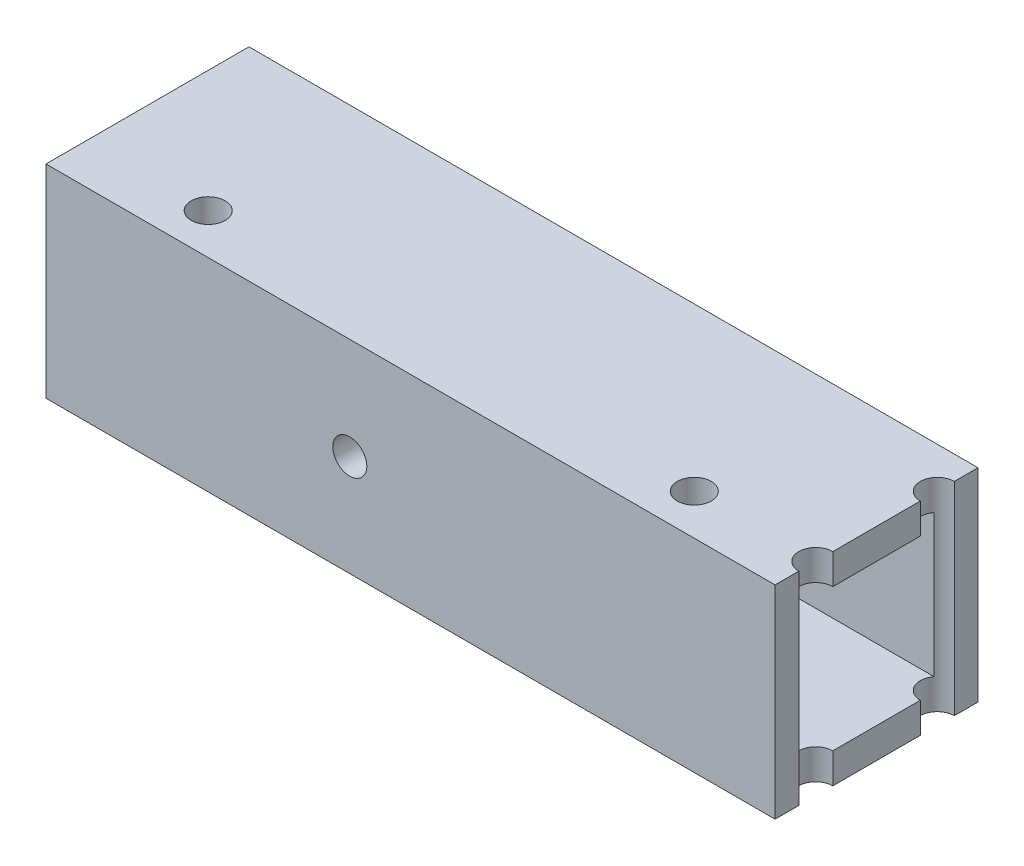
SolidWorks part; units mm, degrees
ref_plane "Front Plane" through (0, 0, 0) normal (0, 0, 1) x (1, 0, 0)
ref_plane "Top Plane" through (0, 0, 0) normal (0, 1, 0) x (1, 0, 0)
ref_plane "Right Plane" through (0, 0, 0) normal (1, 0, 0) x (0, 0, -1)
ref_plane "Plane1" through (0, -110.3, 0) normal (0, -1, 0) x (1, 0, 0)
sketch "Sketch1" plane through (0, -110.3, 0) normal (0, -1, 0) x (1, 0, 0)
  line L0 (-150, 132.8) -> (-150, 107.2)
  line L1 (-150, 107.2) -> (-30, 107.2)
  line L2 (-30, 112.8) -> (-30, 127.2)
  line L3 (-30, 132.8) -> (-150, 132.8)
  arc A0 (-30, 107.2) -> (-30, 112.8) centre (-30, 110) ccw
  arc A1 (-30, 127.2) -> (-30, 132.8) centre (-30, 130) ccw
extrude "Boss-Extrude1" add sketch "Sketch1" against normal blind 5
sketch "Sketch2" plane through (0, 0, 107.2) normal (0, 0, -1) x (-1, 0, 0)
  line L0 (30, -110.3) -> (30, -105.3)
  line L1 (30, -105.3) -> (150, -105.3)
  line L2 (150, -105.3) -> (150, -110.3)
  line L3 (150, -110.3) -> (30, -110.3)
extrude "Boss-Extrude2" add sketch "Sketch2" along normal blind 3.9
sketch "Sketch3" plane through (0, 0, 132.8) normal (0, 0, 1) x (1, 0, 0)
  line L0 (-30, -110.3) -> (-150, -110.3)
  line L1 (-150, -110.3) -> (-150, -105.3)
  line L2 (-150, -105.3) -> (-30, -105.3)
  line L3 (-30, -105.3) -> (-30, -110.3)
extrude "Boss-Extrude3" add sketch "Sketch3" along normal blind 3.9
sketch "Sketch4" plane through (0, -110.3, 0) normal (0, -1, 0) x (1, 0, 0)
  line L0 (-32.2249, 131.7) -> (-150, 131.7)
  line L1 (-150, 131.7) -> (-150, 136.7)
  line L2 (-150, 136.7) -> (-30, 136.7)
  line L3 (-30, 136.7) -> (-30, 132.8)
  arc A0 (-30, 132.8) -> (-32.2249, 131.7) centre (-30, 130) cw
extrude "Boss-Extrude4" add sketch "Sketch4" along normal blind 23.4
sketch "Sketch5" plane through (0, -110.3, 0) normal (0, -1, 0) x (1, 0, 0)
  line L0 (-150, 108.3) -> (-32.2249, 108.3)
  line L1 (-30, 107.2) -> (-30, 103.3)
  line L2 (-30, 103.3) -> (-150, 103.3)
  line L3 (-150, 103.3) -> (-150, 108.3)
  arc A0 (-32.2249, 108.3) -> (-30, 107.2) centre (-30, 110) cw
extrude "Boss-Extrude5" add sketch "Sketch5" along normal blind 23.4
sketch "Sketch6" plane through (0, -133.7, 0) normal (0, -1, 0) x (1, 0, 0)
  line L0 (-30, 107.2) -> (-30, 103.3)
  line L1 (-30, 103.3) -> (-150, 103.3)
  line L2 (-150, 103.3) -> (-150, 136.7)
  line L3 (-150, 136.7) -> (-30, 136.7)
  line L4 (-30, 136.7) -> (-30, 132.8)
  line L5 (-30, 127.2) -> (-30, 112.8)
  arc A0 (-30, 132.8) -> (-30, 127.2) centre (-30, 130) cw
  arc A1 (-30, 112.8) -> (-30, 107.2) centre (-30, 110) cw
extrude "Boss-Extrude6" add sketch "Sketch6" along normal blind 5
ref_plane "Plane2" through (0, 0, 110) normal (0, 0, 1) x (1, 0, 0)
sketch "Sketch7" plane through (0, 0, 110) normal (0, 0, 1) x (1, 0, 0)
  line L0 (-27.2, -105.3) -> (-30, -105.3)
  line L1 (-30, -105.3) -> (-30, -138.7)
  line L2 (-30, -138.7) -> (-27.2, -138.7)
  line L3 (-27.2, -138.7) -> (-27.2, -105.3)
  line L4 (-30, -105.3) -> (-30, -138.7) construction
revolve "Cut-Revolve1" cut sketch "Sketch7" angle 360 about L4
ref_plane "Plane3" through (0, 0, 130) normal (0, 0, 1) x (1, 0, 0)
sketch "Sketch8" plane through (0, 0, 130) normal (0, 0, 1) x (1, 0, 0)
  line L0 (-27.2, -105.3) -> (-30, -105.3)
  line L1 (-30, -105.3) -> (-30, -138.7)
  line L2 (-30, -138.7) -> (-27.2, -138.7)
  line L3 (-27.2, -138.7) -> (-27.2, -105.3)
  line L4 (-30, -105.3) -> (-30, -138.7) construction
revolve "Cut-Revolve2" cut sketch "Sketch8" angle 360 about L4
hole_wizard "Ø5.6 (5.6) Diameter Hole1" positions "Sketch10" profile "Sketch9" hole size "Ø5.6" standard "ANSI Metric"
sketch "Sketch10" plane through (0, -105.3, 0) normal (0, 1, 0) x (1, 0, 0)
  point P0 (-50, -130)
  point P1 (-130, -130)
sketch "Sketch9" plane through (-50, -105.3, 130) normal (1, 0, 0) x (0, 0, 1)
  line L0 (0, 0) -> (0, 33.4)
  line L1 (0, 33.4) -> (2.8, 33.4)
  line L2 (2.8, 33.4) -> (2.8, 0)
  line L5 (2.8, 0) -> (0, 0)
  line L11 (0, -6.35) -> (0, 107.95) construction
  dimension "Thru Hole Dia." = 5.6
  dimension "Thru Hole Depth" = 33.4
hole_wizard "Ø5.6 (5.6) Diameter Hole2" positions "Sketch12" profile "Sketch11" hole size "Ø5.6" standard "ANSI Metric"
sketch "Sketch12" plane through (0, 0, 131.7) normal (0, 0, -1) x (-1, 0, 0)
  point P0 (100, -122)
sketch "Sketch11" plane through (-100, -122, 131.7) normal (1, 0, 0) x (0, 1, 0)
  line L0 (0, 0) -> (0, 5)
  line L1 (0, 5) -> (2.8, 5)
  line L2 (2.8, 5) -> (2.8, 0)
  line L5 (2.8, 0) -> (0, 0)
  line L11 (0, -6.35) -> (0, 107.95) construction
  dimension "Thru Hole Dia." = 5.6
  dimension "Thru Hole Depth" = 5
hole_wizard "Ø5.6 (5.6) Diameter Hole3" positions "Sketch14" profile "Sketch13" hole size "Ø5.6" standard "ANSI Metric"
sketch "Sketch14" plane through (0, 0, 103.3) normal (0, 0, -1) x (-1, 0, 0)
  point P0 (100, -122)
sketch "Sketch13" plane through (-100, -122, 103.3) normal (1, 0, 0) x (0, 1, 0)
  line L0 (0, 0) -> (0, 33.4)
  line L1 (0, 33.4) -> (2.8, 33.4)
  line L2 (2.8, 33.4) -> (2.8, 0)
  line L5 (2.8, 0) -> (0, 0)
  line L11 (0, -6.35) -> (0, 107.95) construction
  dimension "Thru Hole Dia." = 5.6
  dimension "Thru Hole Depth" = 33.4
